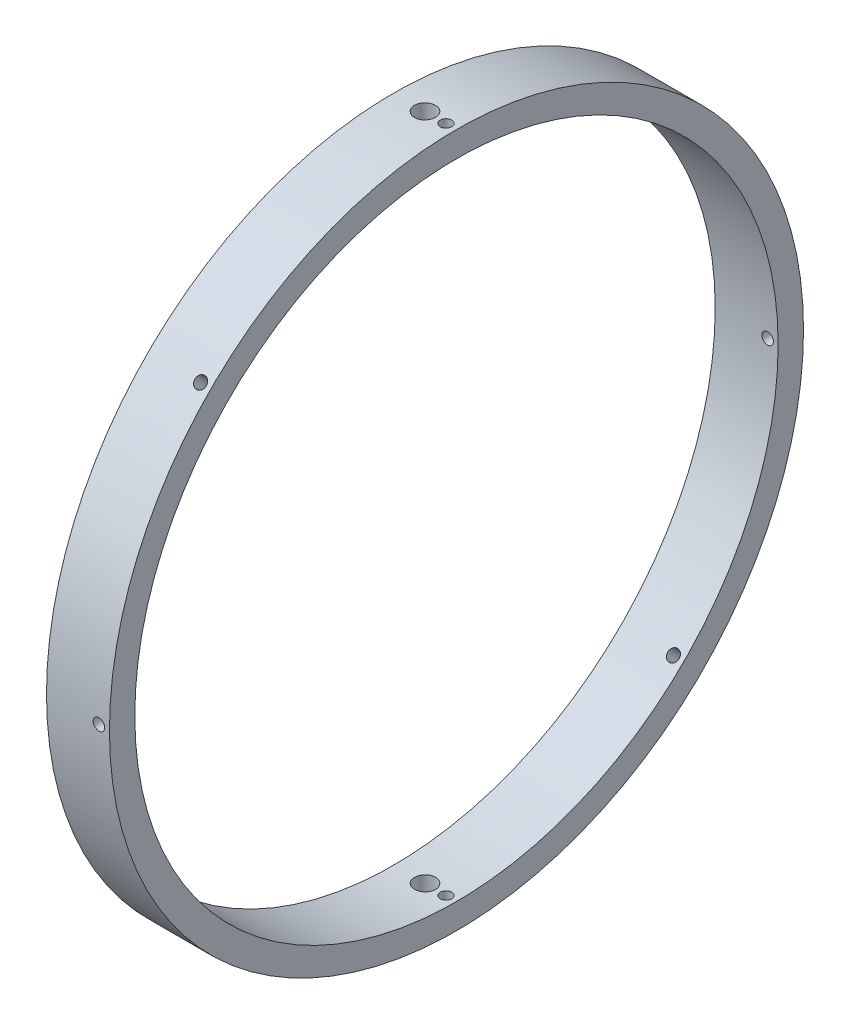
SolidWorks part; units mm, degrees
ref_plane "Front Plane" through (0, 0, 0) normal (0, 0, 1) x (1, 0, 0)
ref_plane "Top Plane" through (0, 0, 0) normal (0, 1, 0) x (1, 0, 0)
ref_plane "Right Plane" through (0, 0, 0) normal (1, 0, 0) x (0, 0, -1)
sketch "Mount Sketch" plane through (0, 0, 0) normal (0, 0, 1) x (1, 0, 0)
  line L0 (-108, 0) -> (12, 0) construction
  line L1 (-57, 92) -> (-39, 92)
  line L2 (-39, 92) -> (-39, 99.25)
  line L3 (-39, 99.25) -> (-57, 99.25)
  line L4 (-57, 99.25) -> (-57, 92)
revolve "Mount" add sketch "Mount Sketch" angle 360 about L0
ref_axis "Engine Axis" through (-38.1, 0, 0) along (-1, 0, 0)
sketch "Pin Hole Sketch" plane through (0, 0, 0) normal (0, 0, 1) x (1, 0, 0)
  line L0 (-48, 82) -> (-48, 109.25) construction
  line L1 (-48, 91) -> (-45, 91)
  line L2 (-45, 91) -> (-45, 100.25)
  line L3 (-45, 100.25) -> (-48, 100.25)
  line L4 (-48, 100.25) -> (-48, 91)
revolve "Pin Hole" cut sketch "Pin Hole Sketch" angle 360 about L0
pattern_circular "Pin Holes x2" count 2 over 360 about axis through (-48, 0, 0) along (0, 1, 0) of "Pin Hole"
sketch "Screw Hole Sketch" plane through (0, 0, 0) normal (0, 0, 1) x (1, 0, 0)
  line L0 (-42, 82) -> (-42, 109.25) construction
  line L1 (-42, 91) -> (-40.35, 91)
  line L2 (-40.35, 91) -> (-40.35, 100.25)
  line L3 (-40.35, 100.25) -> (-42, 100.25)
  line L4 (-42, 100.25) -> (-42, 91)
revolve "Screw Hole" cut sketch "Screw Hole Sketch" angle 360 about L0
pattern_circular "Screw Holes x8" count 8 over 360 about axis through (-38.1, 0, 0) along (-1, 0, 0) of "Screw Hole"
